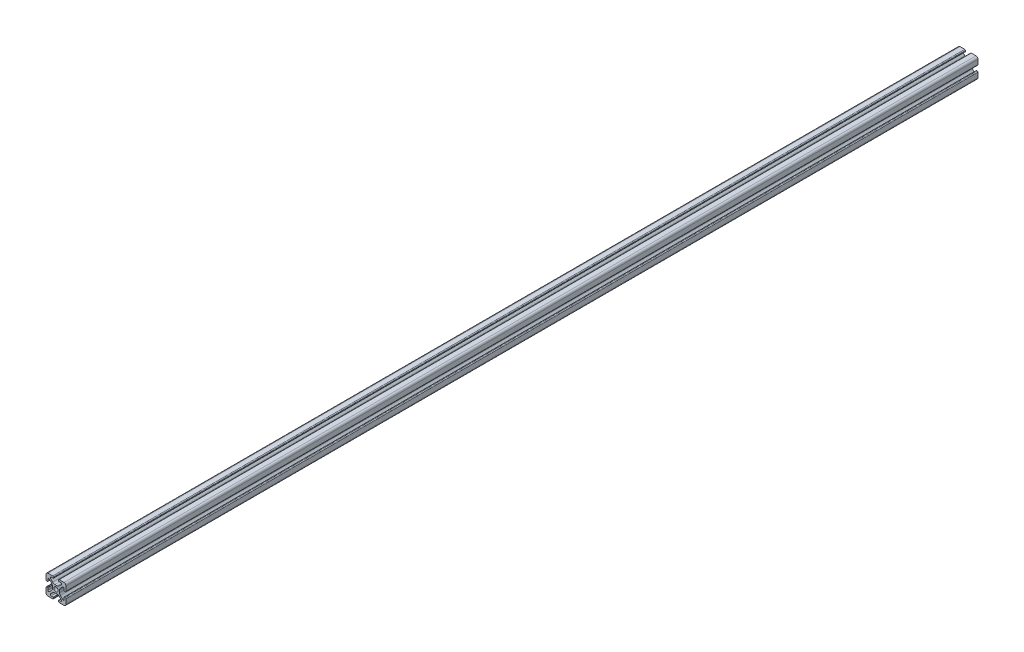
SolidWorks part; units mm, degrees
ref_plane "Front Plane" through (0, 0, 0) normal (0, 0, 1) x (1, 0, 0)
ref_plane "Top Plane" through (0, 0, 0) normal (0, 1, 0) x (1, 0, 0)
ref_plane "Right Plane" through (0, 0, 0) normal (1, 0, 0) x (0, 0, -1)
sketch "Sketch1" plane through (0, 0, 0) normal (0, 0, 1) x (1, 0, 0)
  line L2 (-9.9949, 7.9883) -> (-9.9949, 3.2893)
  line L3 (-7.9883, 9.9949) -> (-3.2893, 9.9949)
  line L4 (-2.5019, 9.2075) -> (-2.5019, 8.4963)
  line L5 (-2.8067, 8.1915) -> (-4.9149, 8.1915)
  line L6 (-5.5076, 6.7606) -> (-3.2528, 4.5058)
  line L7 (-6.7606, 5.5076) -> (-4.5058, 3.2528)
  line L8 (-8.1915, 4.9149) -> (-8.1915, 2.8067)
  line L9 (-8.4963, 2.5019) -> (-9.2075, 2.5019)
  line L11 (-1.1334, 3.6279) -> (1.1334, 3.6279)
  line L12 (-3.6279, 1.1334) -> (-3.6279, -1.1334)
  line L13 (8.4963, 2.5019) -> (9.2075, 2.5019)
  line L14 (8.1915, 4.9149) -> (8.1915, 2.8067)
  line L15 (9.9949, 7.9883) -> (9.9949, 3.2893)
  line L16 (7.9883, 9.9949) -> (3.2893, 9.9949)
  line L17 (2.5019, 9.2075) -> (2.5019, 8.4963)
  line L18 (2.8067, 8.1915) -> (4.9149, 8.1915)
  line L19 (3.6279, 1.1334) -> (3.6279, -1.1334)
  line L20 (5.5076, 6.7606) -> (3.2528, 4.5058)
  line L21 (6.7606, 5.5076) -> (4.5058, 3.2528)
  line L22 (-8.4963, -2.5019) -> (-9.2075, -2.5019)
  line L23 (-8.1915, -4.9149) -> (-8.1915, -2.8067)
  line L24 (-6.7606, -5.5076) -> (-4.5058, -3.2528)
  line L25 (-5.5076, -6.7606) -> (-3.2528, -4.5058)
  line L26 (-2.8067, -8.1915) -> (-4.9149, -8.1915)
  line L27 (-2.5019, -9.2075) -> (-2.5019, -8.4963)
  line L28 (-7.9883, -9.9949) -> (-3.2893, -9.9949)
  line L29 (-9.9949, -7.9883) -> (-9.9949, -3.2893)
  line L30 (9.9949, -7.9883) -> (9.9949, -3.2893)
  line L31 (7.9883, -9.9949) -> (3.2893, -9.9949)
  line L32 (2.5019, -9.2075) -> (2.5019, -8.4963)
  line L33 (2.8067, -8.1915) -> (4.9149, -8.1915)
  line L34 (5.5076, -6.7606) -> (3.2528, -4.5058)
  line L35 (6.7606, -5.5076) -> (4.5058, -3.2528)
  line L36 (8.1915, -4.9149) -> (8.1915, -2.8067)
  line L37 (8.4963, -2.5019) -> (9.2075, -2.5019)
  line L38 (-1.1334, -3.6279) -> (1.1334, -3.6279)
  circle A0 centre (0, 0) radius 2.1463
  arc A1 (-9.9949, 7.9883) -> (-7.9883, 9.9949) centre (-7.9883, 7.9883) cw
  arc A2 (-6.7606, 5.5076) -> (-8.1915, 4.9149) centre (-7.3533, 4.9149) ccw
  arc A3 (-4.9149, 8.1915) -> (-5.5076, 6.7606) centre (-4.9149, 7.3533) ccw
  arc A4 (-3.2893, 9.9949) -> (-2.5019, 9.2075) centre (-3.2893, 9.2075) cw
  arc A5 (-9.9949, 3.2893) -> (-9.2075, 2.5019) centre (-9.2075, 3.2893) ccw
  arc A6 (-8.1915, 2.8067) -> (-8.4963, 2.5019) centre (-8.4963, 2.8067) cw
  arc A7 (-2.5019, 8.4963) -> (-2.8067, 8.1915) centre (-2.8067, 8.4963) cw
  arc A8 (-1.1334, 3.6279) -> (-3.2528, 4.5058) centre (-1.1334, 6.6251) cw
  arc A9 (-3.6279, 1.1334) -> (-4.5058, 3.2528) centre (-6.6251, 1.1334) ccw
  arc A10 (8.1915, 2.8067) -> (8.4963, 2.5019) centre (8.4963, 2.8067) ccw
  arc A11 (9.9949, 3.2893) -> (9.2075, 2.5019) centre (9.2075, 3.2893) cw
  arc A12 (9.9949, 7.9883) -> (7.9883, 9.9949) centre (7.9883, 7.9883) ccw
  arc A13 (3.2893, 9.9949) -> (2.5019, 9.2075) centre (3.2893, 9.2075) ccw
  arc A14 (2.5019, 8.4963) -> (2.8067, 8.1915) centre (2.8067, 8.4963) ccw
  arc A15 (1.1334, 3.6279) -> (3.2528, 4.5058) centre (1.1334, 6.6251) ccw
  arc A16 (3.6279, 1.1334) -> (4.5058, 3.2528) centre (6.6251, 1.1334) cw
  arc A17 (6.7606, 5.5076) -> (8.1915, 4.9149) centre (7.3533, 4.9149) cw
  arc A18 (4.9149, 8.1915) -> (5.5076, 6.7606) centre (4.9149, 7.3533) cw
  arc A19 (-3.6279, -1.1334) -> (-4.5058, -3.2528) centre (-6.6251, -1.1334) cw
  arc A20 (-1.1334, -3.6279) -> (-3.2528, -4.5058) centre (-1.1334, -6.6251) ccw
  arc A21 (-2.5019, -8.4963) -> (-2.8067, -8.1915) centre (-2.8067, -8.4963) ccw
  arc A22 (-8.1915, -2.8067) -> (-8.4963, -2.5019) centre (-8.4963, -2.8067) ccw
  arc A23 (-9.9949, -3.2893) -> (-9.2075, -2.5019) centre (-9.2075, -3.2893) cw
  arc A24 (-3.2893, -9.9949) -> (-2.5019, -9.2075) centre (-3.2893, -9.2075) ccw
  arc A25 (-4.9149, -8.1915) -> (-5.5076, -6.7606) centre (-4.9149, -7.3533) cw
  arc A26 (-6.7606, -5.5076) -> (-8.1915, -4.9149) centre (-7.3533, -4.9149) cw
  arc A27 (-9.9949, -7.9883) -> (-7.9883, -9.9949) centre (-7.9883, -7.9883) ccw
  arc A28 (9.9949, -7.9883) -> (7.9883, -9.9949) centre (7.9883, -7.9883) cw
  arc A29 (6.7606, -5.5076) -> (8.1915, -4.9149) centre (7.3533, -4.9149) ccw
  arc A30 (4.9149, -8.1915) -> (5.5076, -6.7606) centre (4.9149, -7.3533) ccw
  arc A31 (3.2893, -9.9949) -> (2.5019, -9.2075) centre (3.2893, -9.2075) cw
  arc A32 (9.9949, -3.2893) -> (9.2075, -2.5019) centre (9.2075, -3.2893) ccw
  arc A33 (8.1915, -2.8067) -> (8.4963, -2.5019) centre (8.4963, -2.8067) cw
  arc A34 (2.5019, -8.4963) -> (2.8067, -8.1915) centre (2.8067, -8.4963) cw
  arc A35 (1.1334, -3.6279) -> (3.2528, -4.5058) centre (1.1334, -6.6251) cw
  arc A36 (3.6279, -1.1334) -> (4.5058, -3.2528) centre (6.6251, -1.1334) ccw
extrude "Boss-Extrude1" add sketch "Sketch1" along normal mid plane 914.4
